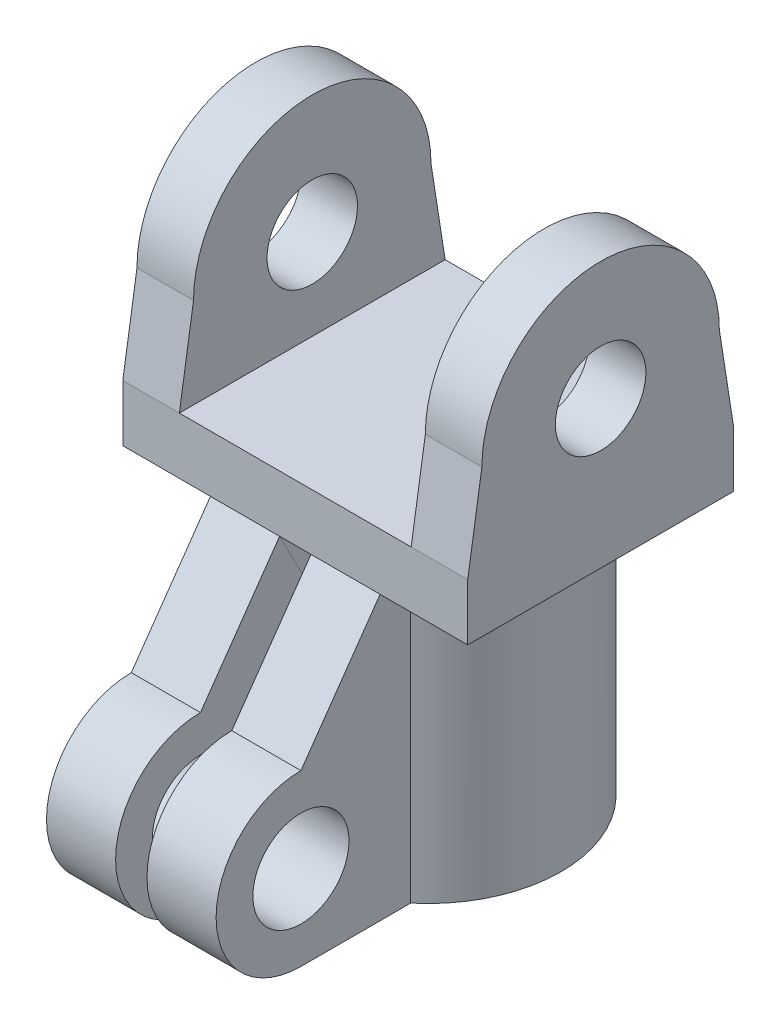
SolidWorks part; units mm, degrees
ref_plane "前视基准面" through (0, 0, 0) normal (0, 0, 1) x (1, 0, 0)
ref_plane "上视基准面" through (0, 0, 0) normal (0, 1, 0) x (1, 0, 0)
ref_plane "右视基准面" through (0, 0, 0) normal (1, 0, 0) x (0, 0, -1)
sketch "草图1" plane through (0, 0, 0) normal (0, 1, 0) x (1, 0, 0)
  circle A0 centre (0, 0) radius 2.7
  circle A1 centre (0, 0) radius 4.7
  dimension "D1" = 5.4
  dimension "D2" = 9.4
extrude "凸台-拉伸1" add sketch "草图1" along normal blind 10
sketch "草图2" plane through (0, 10, 0) normal (0, 1, 0) x (1, 0, 0)
  line L1 (-6.1, -4.7) -> (6.1, -4.7)
  line L2 (-6.1, -4.7) -> (-6.1, 4.7)
  line L3 (-6.1, 4.7) -> (6.1, 4.7)
  line L4 (6.1, -4.7) -> (6.1, 4.7)
  line L5 (-6.1, -4.7) -> (6.1, 4.7) construction
  line L6 (-6.1, 4.7) -> (6.1, -4.7) construction
  circle A0 centre (0, 0) radius 4.7 construction
  point P0 (0, 0)
  dimension "D1" = 12.2
extrude "凸台-拉伸2" add sketch "草图2" along normal blind 2
sketch "草图3" plane through (-6.1, 0, 0) normal (-1, 0, 0) x (0, 0, 1)
  line L3 (0, 20.2944) -> (0, -2.8579) construction
  line L4 (-4.7, 12) -> (4.7, 12)
  line L5 (-4.2, 15.2) -> (-4.7, 12)
  line L6 (4.2, 15.2) -> (4.7, 12)
  arc A0 (4.2, 15.2) -> (-4.2, 15.2) centre (0, 15.2) ccw
  circle A1 centre (0, 15.2) radius 1.6
  dimension "D2" = 8.4
  dimension "D1" = 3.2
extrude "凸台-拉伸3" add sketch "草图3" against normal blind 2
mirror "镜向1" about plane through (0, 0, 0) normal (1, 0, 0) of "凸台-拉伸2", "凸台-拉伸3"
sketch "草图4" plane through (0, 0, 0) normal (1, 0, 0) x (0, 0, -1)
  line L0 (3.8082, 3) -> (-10.8285, 3) construction
  line L6 (-5.5, 8.1815) -> (-5.5, -0.4327) construction
  line L7 (-4.7, 10) -> (0, 10)
  line L8 (-4.7, 10) -> (4.7, 10) construction
  line L9 (0, 10) -> (0, 0)
  line L10 (0, 0) -> (-7.5, 0)
  line L11 (-7.5, 6) -> (-4.7, 10)
  circle A2 centre (-7.5, 3) radius 1.7
  arc A3 (-7.5, 6) -> (-7.5, 0) centre (-7.5, 3) ccw
  dimension "D1" = 2
  dimension "D3" = 3
  dimension "D2" = 3.4
  dimension "D4" = 6
extrude "凸台-拉伸4" add sketch "草图4" along normal blind 3 and the other way blind 3 separate body
sketch "草图5" plane through (0, 0, 0) normal (0, -1, 0) x (1, 0, 0)
  circle A0 centre (0, 0) radius 2.7 construction
  circle A1 centre (0, 0) radius 2.7
extrude "切除-拉伸1" cut sketch "草图5" against normal blind 6
sketch "草图6" plane through (0, 0, 0) normal (0, 0, 1) x (1, 0, 0)
  line L0 (0, -1.3797) -> (0, 16.8476) construction
  line L8 (-6.1, 10) -> (0, 10) construction
  line L9 (-0.5547, 10) -> (-0.5547, 0)
  line L11 (0.5547, 10) -> (0.5547, 0)
  line L12 (-0.5547, 10) -> (0.5547, 10)
  line L13 (-0.5547, 0) -> (0.5547, 0)
  point P11 (0, 0)
  point P12 (0, 10)
  point P13 (0, 0)
  point P14 (0, 10)
extrude "切除-拉伸2" cut sketch "草图6" along normal through all
